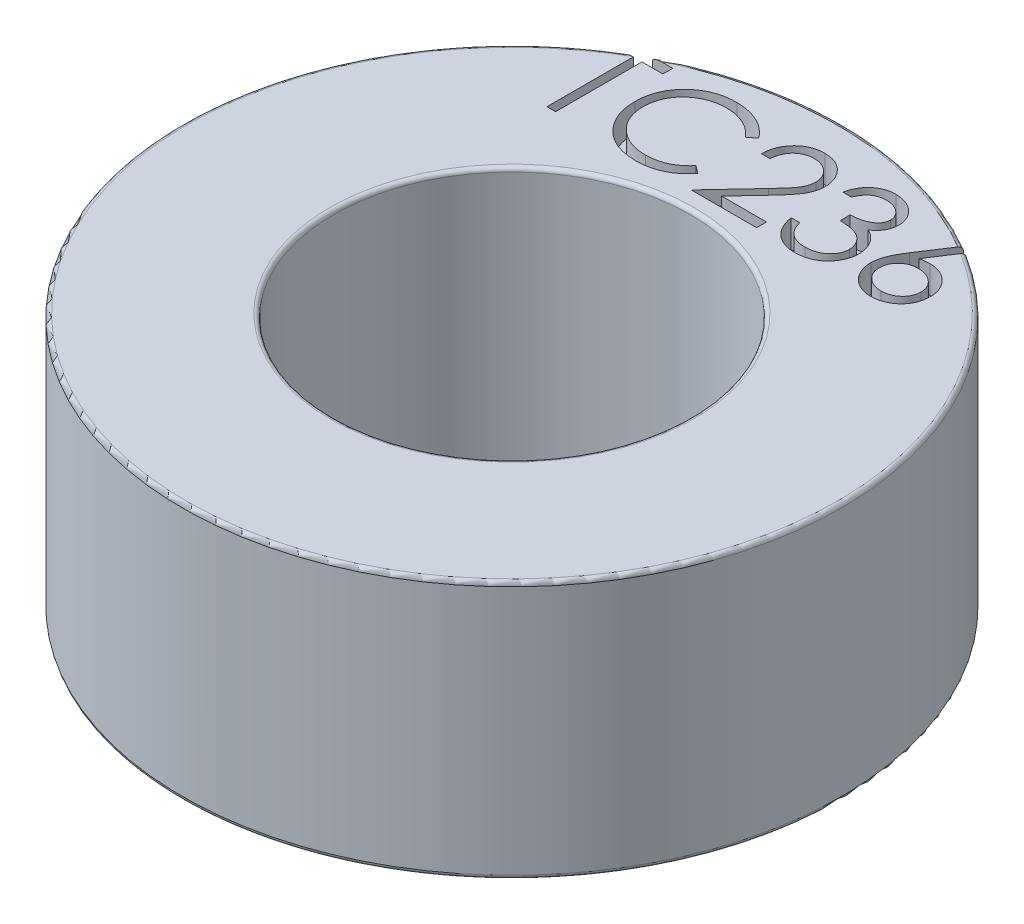
SolidWorks part; units mm, degrees
ref_plane "Front Plane" through (0, 0, 0) normal (0, 0, 1) x (1, 0, 0)
ref_plane "Top Plane" through (0, 0, 0) normal (0, 1, 0) x (1, 0, 0)
ref_plane "Right Plane" through (0, 0, 0) normal (1, 0, 0) x (0, 0, -1)
sketch "Toroidal Core TC236" plane through (0, 0, 0) normal (0, 0, 1) x (1, 0, 0)
  line L0 (0, -8.108) -> (0, 13.3131) construction
  line L2 (6.6461, 0) -> (11.8539, 0)
  line L3 (6.5, 0.1461) -> (6.5, 9.2439)
  line L4 (6.6461, 9.39) -> (11.8539, 9.39)
  line L5 (12, 0.1461) -> (12, 9.2439)
  arc A0 (6.6461, 0) -> (6.5, 0.1461) centre (6.6461, 0.1461) cw
  arc A1 (11.8539, 0) -> (12, 0.1461) centre (11.8539, 0.1461) ccw
  arc A2 (11.8539, 9.39) -> (12, 9.2439) centre (11.8539, 9.2439) cw
  arc A3 (6.5, 9.2439) -> (6.6461, 9.39) centre (6.6461, 9.2439) cw
  point P9 (6.5, 0)
  point P12 (12, 0)
  point P15 (12, 9.39)
  point P18 (6.5, 9.39)
  dimension "D4" = 0.1461
  dimension "D1" = 5.5
  dimension "D2" = 9.39
  dimension "D3" = 6.5
revolve "Revolve2" add sketch "Toroidal Core TC236" angle 360 about L0
sketch "Sketch1" plane through (0, 9.39, 0) normal (0, 1, 0) x (1, 0, 0)
  text T0 "TC236"
extrude "Cut-Extrude1" cut sketch "Sketch1" against normal blind 1
